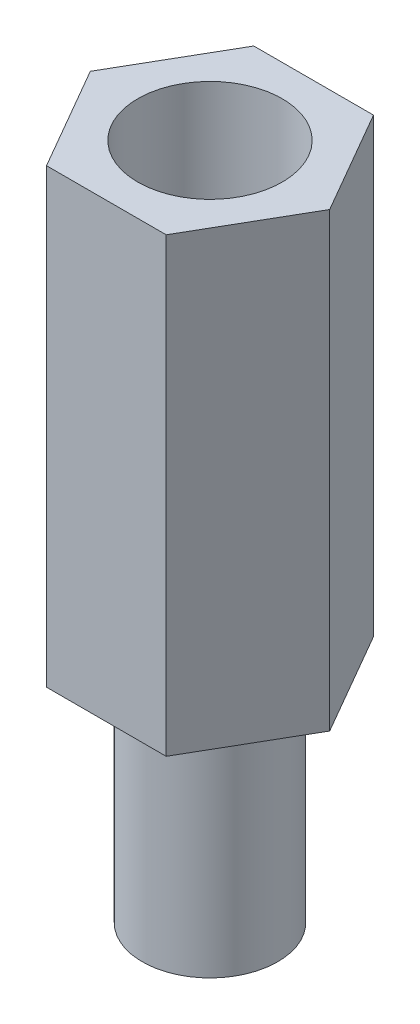
SolidWorks part; units mm, degrees
ref_plane "Front Plane" through (0, 0, 0) normal (0, 0, 1) x (1, 0, 0)
ref_plane "Top Plane" through (0, 0, 0) normal (0, 1, 0) x (1, 0, 0)
ref_plane "Right Plane" through (0, 0, 0) normal (1, 0, 0) x (0, 0, -1)
sketch "Sketch1" plane through (0, 0, 0) normal (0, 1, 0) x (1, 0, 0)
  line L1 (2.65, 0) -> (1.325, 2.295)
  line L2 (1.325, 2.295) -> (-1.325, 2.295)
  line L3 (-1.325, 2.295) -> (-2.65, 0)
  line L4 (-2.65, 0) -> (-1.325, -2.295)
  line L5 (-1.325, -2.295) -> (1.325, -2.295)
  line L6 (1.325, -2.295) -> (2.65, 0)
  circle A0 centre (0, 0) radius 2.295 construction
  dimension "D1" = 5.3
extrude "Boss-Extrude1" add sketch "Sketch1" along normal blind 10
sketch "Sketch2" plane through (0, 10, 0) normal (0, 1, 0) x (1, 0, 0)
  circle A0 centre (0, 0) radius 1.6
  dimension "D1" = 3.2
extrude "Cut-Extrude1" cut sketch "Sketch2" against normal blind 5
sketch "Sketch3" plane through (0, 0, 0) normal (0, -1, 0) x (1, 0, 0)
  circle A0 centre (0, 0) radius 1.5
  dimension "D1" = 3
extrude "Boss-Extrude2" add sketch "Sketch3" along normal blind 5
